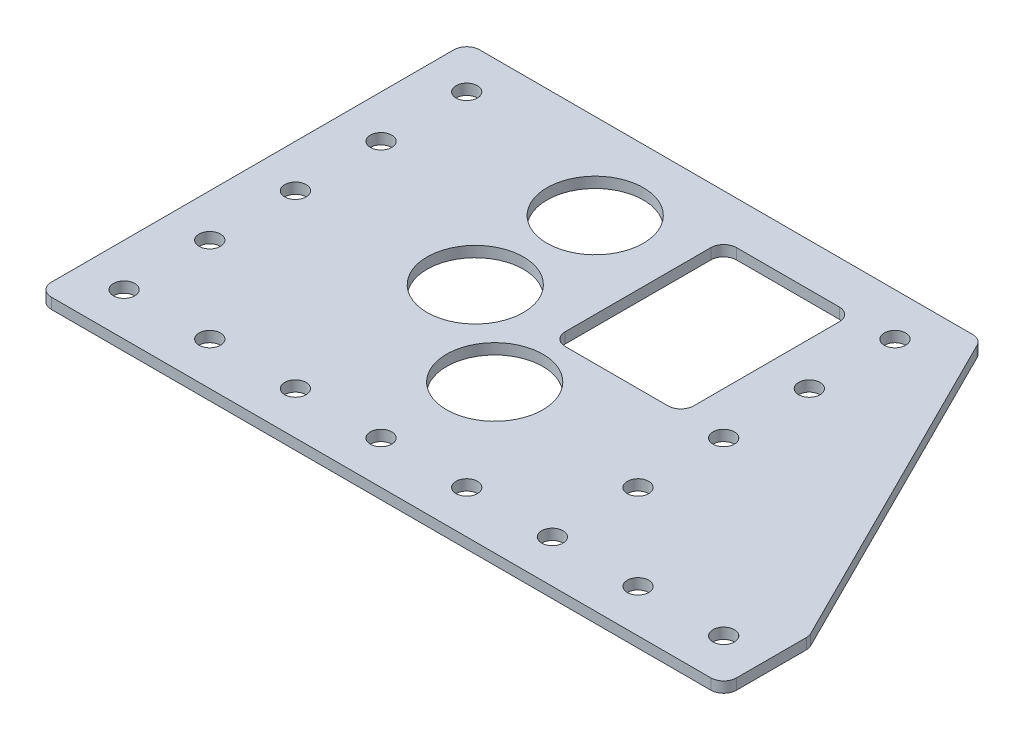
SolidWorks part; units mm, degrees
ref_plane "Front Plane" through (0, 0, 0) normal (0, 0, 1) x (1, 0, 0)
ref_plane "Top Plane" through (0, 0, 0) normal (0, 1, 0) x (1, 0, 0)
ref_plane "Right Plane" through (0, 0, 0) normal (1, 0, 0) x (0, 0, -1)
sketch "Sketch1" plane through (0, 0, 0) normal (0, 1, 0) x (1, 0, 0)
  line L0 (0, 0) -> (0, 127)
  line L1 (0, 127) -> (152.4, 127)
  line L2 (152.4, 127) -> (203.2, 25.4)
  line L3 (203.2, 25.4) -> (203.2, 0)
  line L4 (203.2, 0) -> (0, 0)
  line L5 (88.9, 114.3) -> (127, 114.3)
  line L6 (127, 114.3) -> (127, 63.5)
  line L7 (127, 63.5) -> (88.9, 63.5)
  line L8 (88.9, 63.5) -> (88.9, 114.3)
  line L9 (152.4, -873) -> (152.4, 49127) construction
  line L10 (12.7, 12.7) -> (38.1, 12.7) construction
  line L11 (12.7, 12.7) -> (12.7, 38.1) construction
  circle A0 centre (63.5, 101.6) radius 14.2875
  circle A1 centre (63.5, 66.04) radius 14.2875
  circle A2 centre (91.3602, 43.942) radius 14.2875
  circle A4 centre (12.7, 12.7) radius 3.175
  circle A5 centre (38.1, 12.7) radius 3.175
  circle A6 centre (63.5, 12.7) radius 3.175
  circle A7 centre (88.9, 12.7) radius 3.175
  circle A8 centre (114.3, 12.7) radius 3.175
  circle A9 centre (139.7, 12.7) radius 3.175
  circle A10 centre (165.1, 12.7) radius 3.175
  circle A11 centre (190.5, 12.7) radius 3.175
  circle A12 centre (12.7, 38.1) radius 3.175
  circle A13 centre (12.7, 63.5) radius 3.175
  circle A14 centre (12.7, 88.9) radius 3.175
  circle A15 centre (12.7, 114.3) radius 3.175
  circle A16 centre (139.7, 38.1) radius 3.175
  circle A17 centre (139.7, 63.5) radius 3.175
  circle A18 centre (139.7, 88.9) radius 3.175
  circle A19 centre (139.7, 114.3) radius 3.175
  dimension "D9" = 28.575
  dimension "D12" = 28.575
  dimension "D15" = 28.575
  dimension "D18" = 6.35
  dimension "D1" = 152.4
  dimension "D2" = 203.2
  dimension "D3" = 127
  dimension "D4" = 25.4
  dimension "D5" = 25.4
  dimension "D6" = 38.1
  dimension "D7" = 50.8
  dimension "D8" = 63.5
  dimension "D10" = 25.4
  dimension "D11" = 63.5
  dimension "D13" = 35.56
  dimension "D14" = 63.5
  dimension "D16" = 35.56
  dimension "D17" = 83.058
  dimension "D19" = 12.7
  dimension "D20" = 12.7
  dimension "D22" = 25.4
  dimension "D24" = 25.4
  dimension "D21" = 8
  dimension "D23" = 5
  dimension "D25" = 5
extrude "Boss-Extrude1" add sketch "Sketch1" along normal blind 3.175
fillet "Fillet1" radius 3.81 9 edges at (203.2, 1.5875, -25.4) (0, 1.5875, -127) (0, 1.5875, 0) (203.2, 1.5875, 0) (152.4, 1.5875, -127) (88.9, 1.5875, -63.5) (127, 1.5875, -63.5) (127, 1.5875, -114.3) (88.9, 1.5875, -114.3)
